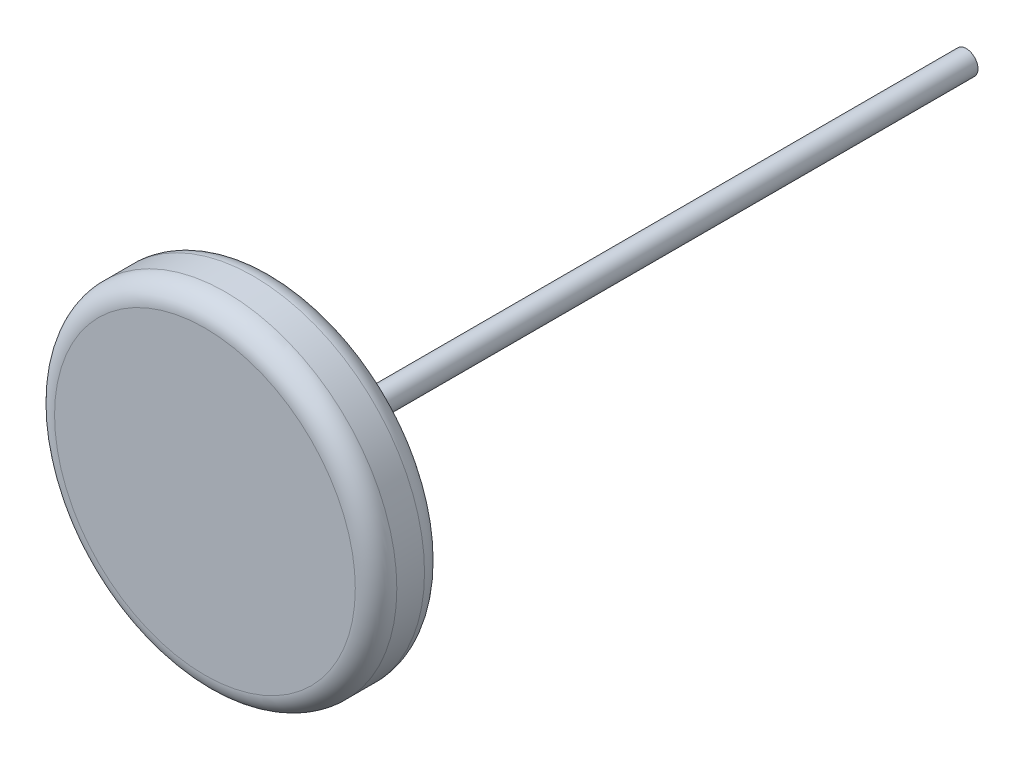
SolidWorks part; units mm, degrees
ref_plane "Front Plane" through (0, 0, 0) normal (0, 0, 1) x (1, 0, 0)
ref_plane "Top Plane" through (0, 0, 0) normal (0, 1, 0) x (1, 0, 0)
ref_plane "Right Plane" through (0, 0, 0) normal (1, 0, 0) x (0, 0, -1)
sketch "Sketch1" plane through (0, 0, 0) normal (0, 0, 1) x (1, 0, 0)
  circle A0 centre (0, 0) radius 1.7
  point P2 (0, 0)
  dimension "D1" = 3.4
extrude "Boss-Extrude1" add sketch "Sketch1" along normal blind 100
sketch "Sketch2" plane through (0, 0, 100) normal (0, 0, 1) x (1, 0, 0)
  circle A0 centre (0, 0) radius 24.7273
extrude "Boss-Extrude2" add sketch "Sketch2" along normal blind 10
fillet "Fillet2" radius 3 3 edges at (1.7, 0, 100) (24.7273, 0, 100) (24.7273, 0, 110)
